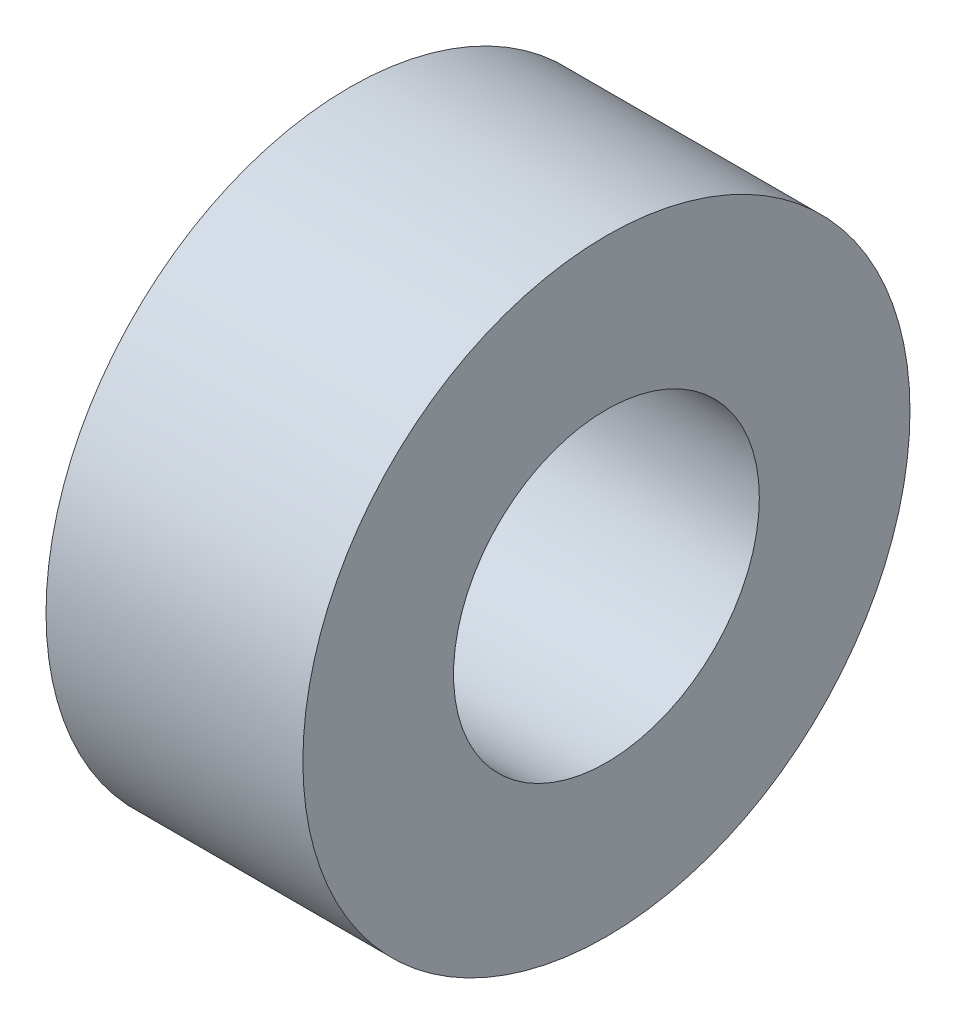
SolidWorks part; units mm, degrees
material "Hardboard"
ref_plane "Front Plane" through (0, 0, 0) normal (0, 0, 1) x (1, 0, 0)
ref_plane "Top Plane" through (0, 0, 0) normal (0, 1, 0) x (1, 0, 0)
ref_plane "Right Plane" through (0, 0, 0) normal (1, 0, 0) x (0, 0, -1)
sketch "Sketch2" plane through (0, 0, 0) normal (1, 0, 0) x (0, 0, -1)
  circle A0 centre (0, 0) radius 2.3813
  circle A1 centre (0, 0) radius 4.7272
  dimension "D1" = 4.7625
extrude "Boss-Extrude1" add sketch "Sketch2" along normal mid plane 4
